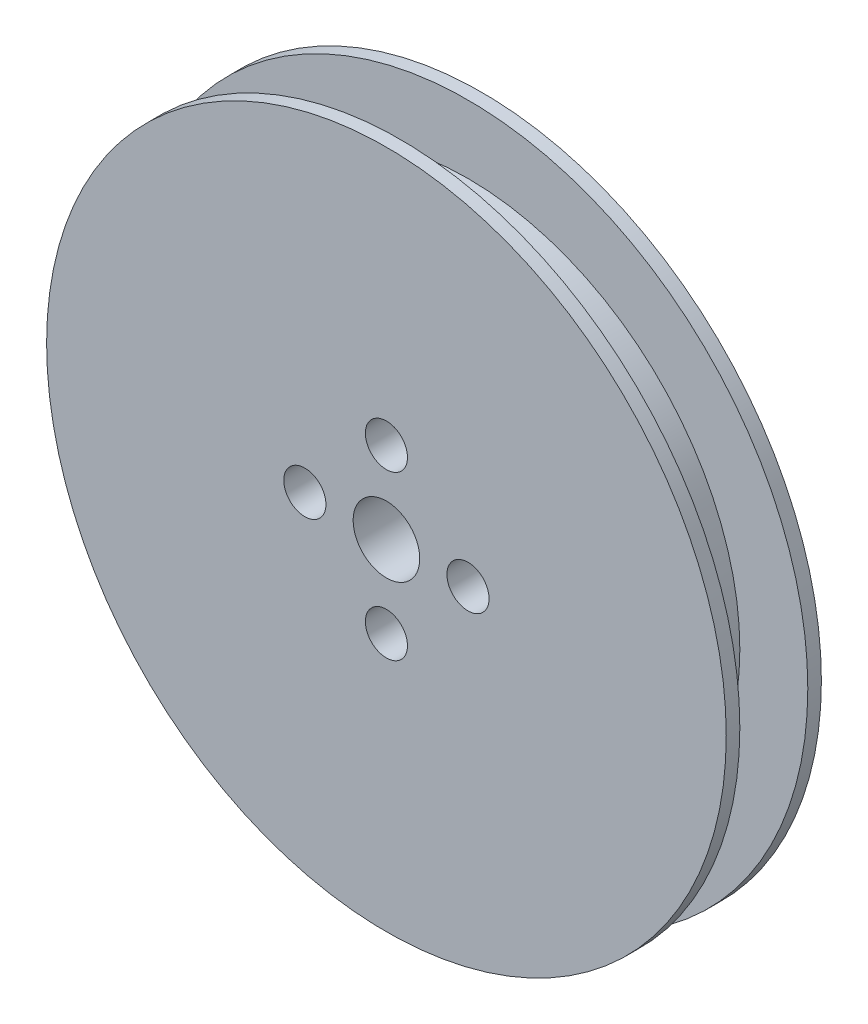
SolidWorks part; units mm, degrees
ref_plane "Front Plane" through (0, 0, 0) normal (0, 0, 1) x (1, 0, 0)
ref_plane "Top Plane" through (0, 0, 0) normal (0, 1, 0) x (1, 0, 0)
ref_plane "Right Plane" through (0, 0, 0) normal (1, 0, 0) x (0, 0, -1)
sketch "Sketch3" plane through (0, 0, 0) normal (0, 1, 0) x (1, 0, 0)
  line L0 (0, 0) -> (-25, 0)
  line L1 (-25, 0) -> (-25, -1)
  line L2 (-25, -1) -> (-20, -1)
  line L3 (-20, -1) -> (-20, -6)
  line L4 (-20, -6) -> (-25, -6)
  line L5 (-25, -6) -> (-25, -7)
  line L6 (-25, -7) -> (0, -7)
  line L7 (0, -7) -> (0, 0)
revolve "Revolve2" add sketch "Sketch3" angle 360 about L7
sketch "Sketch4" plane through (0, 0, 0) normal (0, 0, -1) x (-1, 0, 0)
  circle A0 centre (0, 0) radius 6 construction
  circle A1 centre (0, 6) radius 1.55
  circle A2 centre (6, 0) radius 1.55
  circle A3 centre (0, -6) radius 1.55
  circle A4 centre (-6, 0) radius 1.55
  circle A5 centre (0, 0) radius 2.45
  point P13 (0, 0)
  dimension "D1" = 4
extrude "Cut-Extrude1" cut sketch "Sketch4" against normal through all
